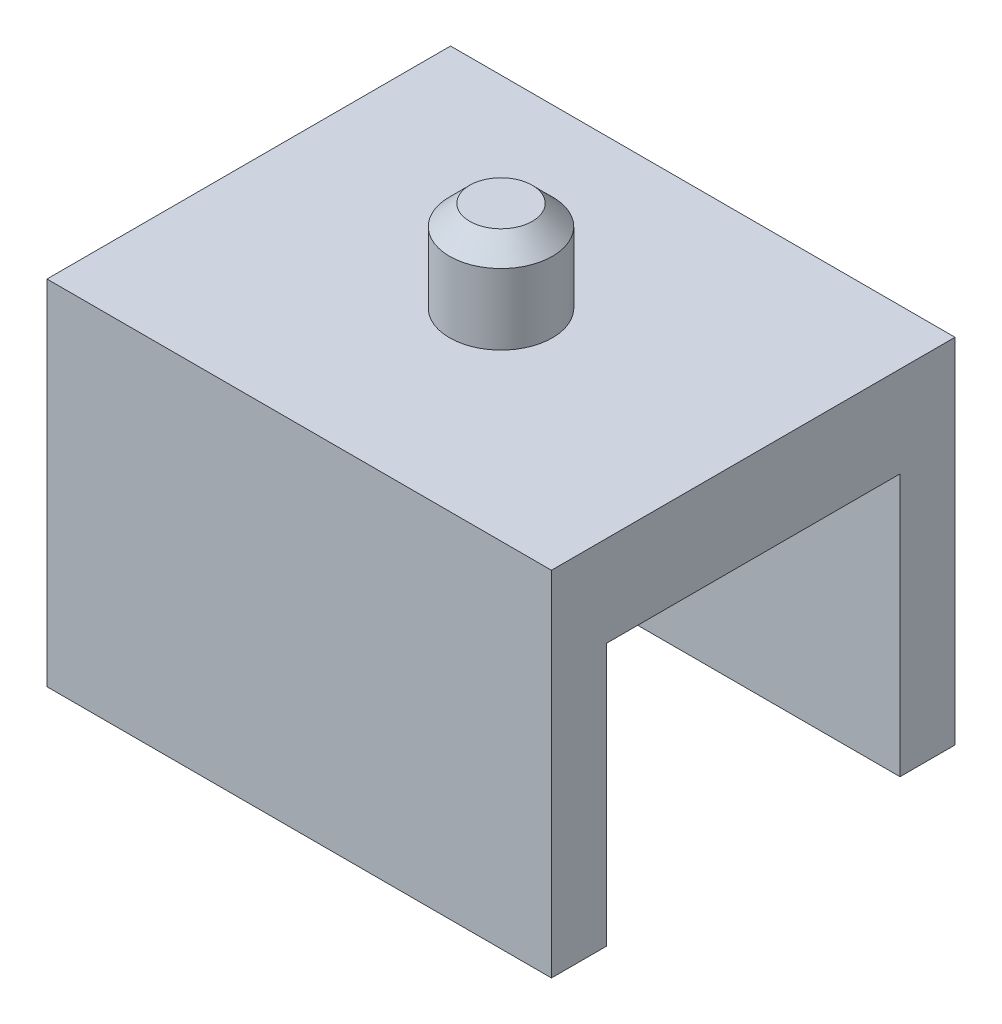
SolidWorks part; units mm, degrees
ref_plane "Top" through (0, 0, 0) normal (0, 0, 1) x (1, 0, 0)
ref_plane "Front" through (0, 0, 0) normal (0, 1, 0) x (1, 0, 0)
ref_plane "Right" through (0, 0, 0) normal (1, 0, 0) x (0, 0, -1)
sketch "Sketch1" plane through (0, 0, 0) normal (0, 0, 1) x (1, 0, 0)
  line L0 (0, 0) -> (0, 17.5)
  line L1 (0, 17.5) -> (25, 17.5)
  line L2 (25, 17.5) -> (25, 0)
  line L3 (25, 0) -> (0, 0)
  dimension "D1" = 25
  dimension "D2" = 17.5
extrude "Boss-Extrude1" add sketch "Sketch1" along normal blind 20
sketch "Sketch2" plane through (0, 0, 0) normal (0, -1, 0) x (1, 0, 0)
  line L0 (0, 2.725) -> (25, 2.725)
  line L1 (0, 20) -> (0, 0) construction
  line L2 (25, 20) -> (25, 0) construction
  line L3 (25, 2.725) -> (25, 17.275)
  line L4 (25, 17.275) -> (0, 17.275)
  line L5 (0, 17.275) -> (0, 2.725)
  line L6 (0, 0) -> (25, 0) construction
  dimension "D1" = 2.725
  dimension "D2" = 14.55
extrude "Cut-Extrude1" cut sketch "Sketch2" against normal blind 13
sketch "Sketch4" plane through (0, 17.5, 0) normal (0, 1, 0) x (1, 0, 0)
  line L0 (25, 0) -> (0, 0) construction
  line L2 (0, -20) -> (0, 0) construction
  circle A0 centre (12.5, -10) radius 2.55
  dimension "D2" = 12.5
  dimension "D3" = 5.1
  dimension "D1" = 10
extrude "Boss-Extrude2" add sketch "Sketch4" along normal blind 4.5
chamfer "Chamfer1" distance 1 angle 45 1 edges at (12.5, 22, 12.55)
sketch "Sketch5" plane through (0, 13, 0) normal (0, -1, 0) x (-1, 0, 0)
  line L0 (-25, 0) -> (0, 0) construction
  line L1 (0, -17.275) -> (0, -2.725) construction
  circle A0 centre (-12.5, -10) radius 1.25
  dimension "D3" = 2.5
  dimension "D1" = 10
  dimension "D2" = 12.5
extrude "Boss-Extrude3" add sketch "Sketch5" along normal blind 3
chamfer "Chamfer2" distance 1 angle 45 1 edges at (13.75, 10, 10)
